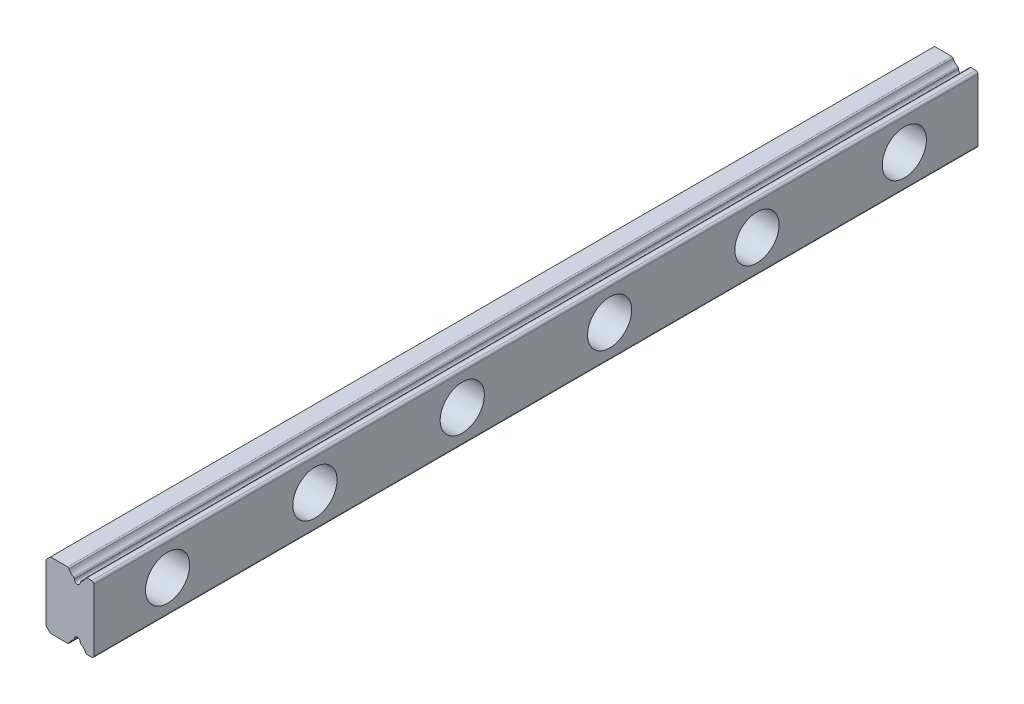
SolidWorks part; units mm, degrees
material "AISI 304"
ref_plane "前视基准面" through (0, 0, 0) normal (0, 0, 1) x (1, 0, 0)
ref_plane "上视基准面" through (0, 0, 0) normal (0, 1, 0) x (1, 0, 0)
ref_plane "右视基准面" through (0, 0, 0) normal (1, 0, 0) x (0, 0, -1)
sketch "草图1" plane through (0, 0, 0) normal (0, 0, 1) x (1, 0, 0)
  line L0 (0, 8.4) -> (0.6, 9)
  line L1 (0.6, 0) -> (2.9423, 0)
  line L2 (0, 0.6) -> (0, 8.4)
  line L3 (0.6, 9) -> (2.9423, 9)
  line L4 (6.5, 0.3) -> (6.5, 8.7)
  line L5 (0, 0.6) -> (0.6, 0)
  line L6 (4.25, 9) -> (4.25, 8) construction
  line L7 (4.25, 9) -> (4.25, 9.3) construction
  line L8 (3.85, 8) -> (3.85, 8.0351)
  line L9 (4.65, 8) -> (4.65, 8.0351)
  line L10 (5.5577, 9) -> (6.2, 9)
  line L11 (6.5, 4.5) -> (0, 4.5) construction
  line L12 (3.85, 8) -> (3.85, 8.0351)
  line L13 (4.65, 8) -> (4.65, 8.0351)
  line L14 (4.25, 0) -> (4.25, -0.3) construction
  line L15 (4.25, 0) -> (4.25, 1) construction
  line L16 (4.65, 1) -> (4.65, 0.9649)
  line L17 (3.85, 1) -> (3.85, 0.9649)
  line L18 (4.65, 1) -> (4.65, 0.9649)
  line L19 (3.85, 1) -> (3.85, 0.9649)
  line L20 (5.5577, 0) -> (6.2, 0)
  arc A0 (3.85, 8) -> (4.65, 8) centre (4.25, 8) ccw
  arc A1 (3.1291, 8.8714) -> (3.7357, 8.2158) centre (4.25, 9.3) ccw
  arc A2 (4.7643, 8.2158) -> (5.3709, 8.8714) centre (4.25, 9.3) ccw
  arc A3 (5.3709, 8.8714) -> (5.5577, 9) centre (5.5577, 8.8) cw
  arc A4 (4.65, 8.0351) -> (4.7643, 8.2158) centre (4.85, 8.0351) cw
  arc A5 (3.85, 8.0351) -> (3.7357, 8.2158) centre (3.65, 8.0351) ccw
  arc A6 (3.1291, 8.8714) -> (2.9423, 9) centre (2.9423, 8.8) ccw
  arc A7 (3.1291, 8.8714) -> (2.9423, 9) centre (2.9423, 8.8) ccw
  arc A8 (5.3709, 8.8714) -> (5.5577, 9) centre (5.5577, 8.8) cw
  arc A9 (4.65, 8.0351) -> (4.7643, 8.2158) centre (4.85, 8.0351) cw
  arc A10 (3.85, 8.0351) -> (3.7357, 8.2158) centre (3.65, 8.0351) ccw
  arc A11 (3.7357, 8.2158) -> (3.1291, 8.8714) centre (4.25, 9.3) cw
  arc A12 (5.3709, 8.8714) -> (4.7643, 8.2158) centre (4.25, 9.3) cw
  arc A13 (5.3709, 0.1286) -> (5.5577, 0) centre (5.5577, 0.2) ccw
  arc A14 (3.1291, 0.1286) -> (2.9423, 0) centre (2.9423, 0.2) cw
  arc A15 (5.3709, 0.1286) -> (4.7643, 0.7842) centre (4.25, -0.3) ccw
  arc A16 (3.7357, 0.7842) -> (3.1291, 0.1286) centre (4.25, -0.3) ccw
  arc A17 (3.85, 0.9649) -> (3.7357, 0.7842) centre (3.65, 0.9649) cw
  arc A18 (4.65, 0.9649) -> (4.7643, 0.7842) centre (4.85, 0.9649) ccw
  arc A19 (3.85, 0.9649) -> (3.7357, 0.7842) centre (3.65, 0.9649) cw
  arc A20 (4.65, 0.9649) -> (4.7643, 0.7842) centre (4.85, 0.9649) ccw
  arc A21 (4.7643, 0.7842) -> (5.3709, 0.1286) centre (4.25, -0.3) cw
  arc A22 (3.1291, 0.1286) -> (3.7357, 0.7842) centre (4.25, -0.3) cw
  arc A23 (3.85, 1) -> (4.65, 1) centre (4.25, 1) cw
  arc A24 (6.2, 0) -> (6.5, 0.3) centre (6.2, 0.3) ccw
  arc A25 (6.2, 9) -> (6.5, 8.7) centre (6.2, 8.7) cw
  point P0 (0, 0)
  point P2 (0, 9)
  point P24 (5.4119, 9)
  point P27 (4.65, 8.1686)
  point P49 (4.65, 0.8314)
  point P50 (5.4119, 0)
  point P53 (6.5, 0)
  dimension "D3" = 1
  dimension "D7" = 0.8
  dimension "D9" = 2.4
  dimension "D10" = 0.2
  dimension "D11" = 0.3
  dimension "D1" = 6.5
  dimension "D2" = 9
  dimension "D4" = 2.25
  dimension "D8" = 0.3
extrude "凸台-拉伸1" add sketch "草图1" along normal blind 120 contours A25 L10 A3 A2 A4 L9 A0 L8 A5 A1 A6 L3 L0 L2 L5 L1 A14 A16 A17 L17 A23 L16 A18 A15 A13 L20 A24 L4
sketch "草图2" plane through (6.5, 0, 0) normal (1, 0, 0) x (0, 0, -1)
  line L0 (-120, 4.5) -> (-110, 4.5) construction
  line L1 (-120, 0.3) -> (-120, 8.7) construction
  line L2 (-110, 4.5) -> (-10, 4.5) construction
  line L3 (-10, 4.5) -> (0, 4.5) construction
  line L4 (0, 0.3) -> (0, 8.7) construction
  line L5 (-10, 4.5) -> (-30, 4.5) construction
  circle A0 centre (-10, 4.5) radius 3
  circle A1 centre (-30, 4.5) radius 3
  circle A2 centre (-50, 4.5) radius 3
  circle A3 centre (-70, 4.5) radius 3
  circle A4 centre (-90, 4.5) radius 3
  circle A5 centre (-110, 4.5) radius 3
  circle A6 centre (-130, 4.5) radius 3
  circle A7 centre (-150, 4.5) radius 3
  circle A8 centre (-170, 4.5) radius 3
  circle A9 centre (-190, 4.5) radius 3
  circle A10 centre (-210, 4.5) radius 3
  circle A11 centre (-230, 4.5) radius 3
  circle A12 centre (-250, 4.5) radius 3
  circle A13 centre (-270, 4.5) radius 3
  circle A14 centre (-290, 4.5) radius 3
  circle A15 centre (-310, 4.5) radius 3
  circle A16 centre (-330, 4.5) radius 3
  circle A17 centre (-350, 4.5) radius 3
  circle A18 centre (-370, 4.5) radius 3
  circle A19 centre (-390, 4.5) radius 3
  circle A20 centre (-410, 4.5) radius 3
  circle A21 centre (-430, 4.5) radius 3
  circle A22 centre (-450, 4.5) radius 3
  circle A23 centre (-470, 4.5) radius 3
  circle A24 centre (-490, 4.5) radius 3
  dimension "D2" = 6
  dimension "D1" = 10
  dimension "D4" = 20
  dimension "D3" = 25
extrude "切除-拉伸1" cut sketch "草图2" against normal blind 4.5
sketch "草图3" plane through (2, 0, 0) normal (1, 0, 0) x (0, 0, -1)
  line L0 (-10, 4.5) -> (-30, 4.5) construction
  circle A0 centre (-10, 4.5) radius 1.75
  circle A1 centre (-30, 4.5) radius 1.75
  circle A2 centre (-50, 4.5) radius 1.75
  circle A3 centre (-70, 4.5) radius 1.75
  circle A4 centre (-90, 4.5) radius 1.75
  circle A5 centre (-110, 4.5) radius 1.75
  circle A6 centre (-130, 4.5) radius 1.75
  circle A7 centre (-150, 4.5) radius 1.75
  circle A8 centre (-170, 4.5) radius 1.75
  circle A9 centre (-190, 4.5) radius 1.75
  circle A10 centre (-210, 4.5) radius 1.75
  circle A11 centre (-230, 4.5) radius 1.75
  circle A12 centre (-250, 4.5) radius 1.75
  circle A13 centre (-270, 4.5) radius 1.75
  circle A14 centre (-290, 4.5) radius 1.75
  circle A15 centre (-310, 4.5) radius 1.75
  circle A16 centre (-330, 4.5) radius 1.75
  circle A17 centre (-350, 4.5) radius 1.75
  circle A18 centre (-370, 4.5) radius 1.75
  circle A19 centre (-390, 4.5) radius 1.75
  circle A20 centre (-410, 4.5) radius 1.75
  circle A21 centre (-430, 4.5) radius 1.75
  circle A22 centre (-450, 4.5) radius 1.75
  circle A23 centre (-470, 4.5) radius 1.75
  circle A24 centre (-490, 4.5) radius 1.75
  dimension "D1" = 3.5
  dimension "D3" = 20
  dimension "D2" = 25
extrude "切除-拉伸2" cut sketch "草图3" against normal through all
